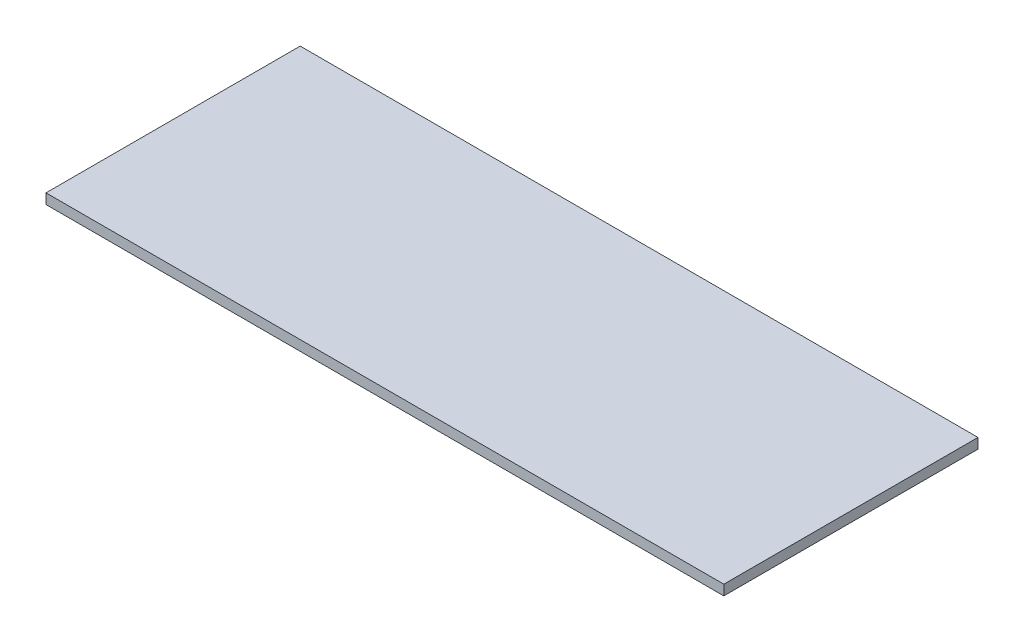
SolidWorks part; units mm, degrees
ref_plane "Front Plane" through (0, 0, 0) normal (0, 0, 1) x (1, 0, 0)
ref_plane "Top Plane" through (0, 0, 0) normal (0, 1, 0) x (1, 0, 0)
ref_plane "Right Plane" through (0, 0, 0) normal (1, 0, 0) x (0, 0, -1)
sketch "Sketch1" plane through (0, 0, 0) normal (0, 1, 0) x (1, 0, 0)
  line L1 (-100, -37.5) -> (100, -37.5)
  line L2 (-100, -37.5) -> (-100, 37.5)
  line L3 (-100, 37.5) -> (100, 37.5)
  line L4 (100, -37.5) -> (100, 37.5)
  line L5 (-100, -37.5) -> (100, 37.5) construction
  line L6 (-100, 37.5) -> (100, -37.5) construction
  point P0 (0, 0)
  dimension "D1" = 200
  dimension "D2" = 75
extrude "Boss-Extrude1" add sketch "Sketch1" along normal blind 3
